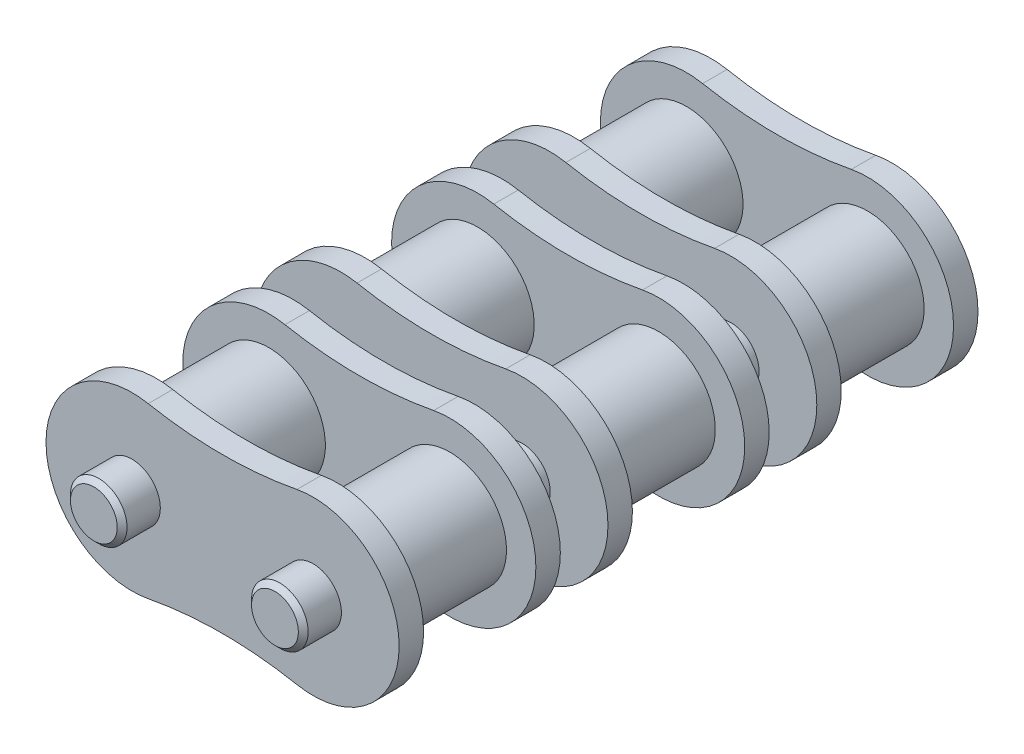
SolidWorks part; units mm, degrees
ref_plane "前视基准面" through (0, 0, 0) normal (0, 0, 1) x (1, 0, 0)
ref_plane "上视基准面" through (0, 0, 0) normal (0, 1, 0) x (1, 0, 0)
ref_plane "右视基准面" through (0, 0, 0) normal (1, 0, 0) x (0, 0, -1)
sketch "草图1" plane through (0, 0, 0) normal (0, 0, 1) x (1, 0, 0)
  line L0 (-12.7, 0) -> (12.7, 0) construction
  line L1 (0, 10.8585) -> (0, -10.8585) construction
  line L2 (12.7, 0) -> (35.31, 0) construction
  line L3 (35.31, 0) -> (51.06, 0) construction
  circle A0 centre (-12.7, 0) radius 12.065
  circle A1 centre (12.7, 0) radius 12.065
  circle A2 centre (0, 66.2389) radius 55.3804
  circle A3 centre (0, -66.2389) radius 55.3804
  circle A4 centre (-12.7, 0) radius 7.94
  circle A5 centre (12.7, 0) radius 7.94
  circle A6 centre (-12.7, 0) radius 3.97
  circle A7 centre (12.7, 0) radius 3.97
  point P16 (104.6, 0)
  point P18 (41.99, 0)
  point P19 (15.7, 0)
  dimension "h2" = 24.13
  dimension "d1" = 15.88
  dimension "d2" = 7.94
  dimension "p" = 25.4
  dimension "h3" = 21.717
  dimension "b2" = 22.61
  dimension "b1" = 15.75
  dimension "b6" = 91.9
  dimension "P1" = 29.29
  dimension "z" = 3
sketch "草图2" plane through (0, 0, 0) normal (0, 0, 1) x (1, 0, 0)
  circle A0 centre (12.7, 0) radius 7.94 construction
  circle A1 centre (-12.7, 0) radius 7.94 construction
  circle A2 centre (12.7, 0) radius 7.94
  circle A3 centre (-12.7, 0) radius 7.94
extrude "拉伸1" add sketch "草图2" along normal mid plane 15.75
sketch "草图3" plane through (0, 0, 7.875) normal (0, 0, 1) x (1, 0, 0)
  circle A0 centre (-12.7, 0) radius 12.065 construction
  arc A1 (-10.4282, 11.8492) -> (-10.4282, -11.8492) centre (-12.7, 0) ccw
  circle A2 centre (12.7, 0) radius 12.065 construction
  arc A3 (10.4282, -11.8492) -> (10.4282, 11.8492) centre (12.7, 0) ccw
  circle A4 centre (0, 66.2389) radius 55.3804 construction
  arc A5 (-10.4282, 11.8492) -> (10.4282, 11.8492) centre (0, 66.2389) ccw
  circle A6 centre (0, -66.2389) radius 55.3804 construction
  arc A7 (10.4282, -11.8492) -> (-10.4282, -11.8492) centre (0, -66.2389) ccw
extrude "拉伸2" add sketch "草图3" along normal blind 3.43
mirror "镜向1" about plane through (0, 0, 0) normal (0, 0, 1) of "拉伸2"
sketch "草图5" plane through (0, 0, 0) normal (0, 0, 1) x (1, 0, 0)
  line L0 (12.7, 0) -> (37.302, -6.3167) construction
  line L1 (-12.7, 0) -> (12.7, 0) construction
  line L2 (-12.7, 0) -> (-776.8532, -96.535)
  line L4 (0, -100.5309) -> (-768.1907, -165.1058) construction
  line L5 (37.302, -6.3167) -> (59.5602, -18.5533) construction
  arc A0 (30.9597, -197.0153) -> (-12.7, 0) centre (0, -100.5309) ccw
  arc A1 (-776.8532, -96.535) -> (-783.5035, -232.504) centre (-768.1907, -165.1058) ccw
  arc A2 (-783.5035, -232.504) -> (30.9597, -197.0153) centre (-441.1553, 1274.3085) ccw
  dimension "R2" = 202.6597
  dimension "R1" = 138.2317
  dimension "a" = 770.9
  dimension "La" = 770.2266
  dimension "L2" = 299.6078
  dimension "L" = 825
  dimension "L1" = 193.0074
curve "组合曲线1"
pattern_linear "阵列(线性)1" count 3 spacing 29.29 along (0, 0, 1) of bodies 105 123 124
sketch "草图4" plane through (0, 0, 0) normal (0, 0, 1) x (1, 0, 0)
  circle A0 centre (12.7, 0) radius 3.97 construction
  circle A1 centre (-12.7, 0) radius 3.97 construction
  circle A2 centre (12.7, 0) radius 3.97
  circle A3 centre (-12.7, 0) radius 3.97
extrude "拉伸3" add sketch "草图4" against normal blind 16.66 and the other way blind 75.24
chamfer "倒角1" distance 0.686 angle 45 4 edges at (16.67, 0, -16.66) (-8.73, 0, -16.66) (16.67, 0, 75.24) (-8.73, 0, 75.24)
equation "\"D1@拉伸1\" = \"b1@草图1\""
equation "\"D1@拉伸2\" = (  \"b2@草图1\" - \"D1@拉伸1\" )  / 2"
equation "\"D1@拉伸3\" = (\"b6@草图1\"-(\"z@草图1\"-1)*\"P1@草图1\")/2"
equation "\"D2@拉伸3\"= \"b6@草图1\"-\"D1@拉伸3\""
equation "\"D1@倒角1\" = \"D1@拉伸2\" / 5"
equation "\"h3@草图1\" = \"h2@草图1\" * 0.9"
equation "\"D3@阵列(线性)1\" = \"P1@草图1\""
equation "\"D1@阵列(线性)1\" =\"z@草图1\""
